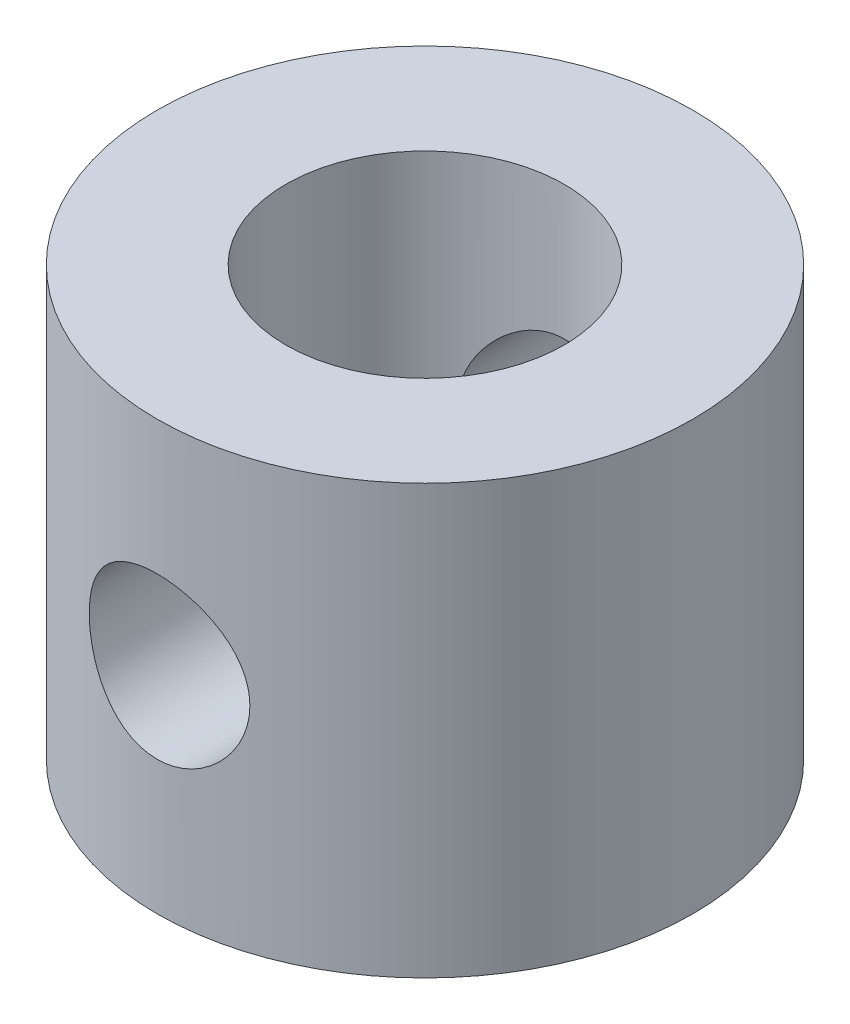
SolidWorks part; units mm, degrees
material "Brass"
ref_plane "Front Plane" through (0, 0, 0) normal (0, 0, 1) x (1, 0, 0)
ref_plane "Top Plane" through (0, 0, 0) normal (0, 1, 0) x (1, 0, 0)
ref_plane "Right Plane" through (0, 0, 0) normal (1, 0, 0) x (0, 0, -1)
sketch "Sketch1" plane through (0, 0, 0) normal (0, 1, 0) x (1, 0, 0)
  circle A0 centre (0, 0) radius 5
  dimension "D1" = 10
extrude "Boss-Extrude1" add sketch "Sketch1" along normal blind 8
sketch "Sketch2" plane through (0, 0, 0) normal (0, 1, 0) x (1, 0, 0)
  circle A0 centre (0, 0) radius 2.6
  dimension "D1" = 5.2
extrude "Cut-Extrude1" cut sketch "Sketch2" against normal mid plane 40
sketch "Sketch3" plane through (0, 0, 0) normal (0, 0, 1) x (1, 0, 0)
  circle A0 centre (0, 4) radius 1.5
  dimension "D2" = 3
  dimension "D1" = 4
extrude "Cut-Extrude2" cut sketch "Sketch3" against normal mid plane 40
